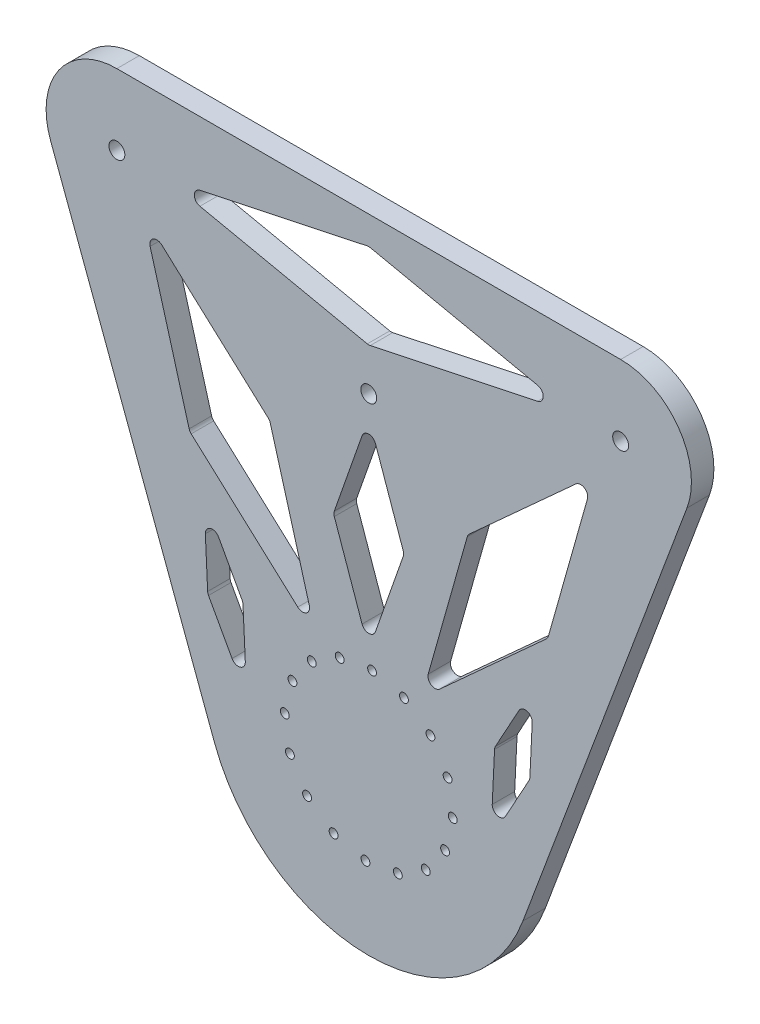
SolidWorks part; units mm, degrees
ref_plane "Front Plane" through (0, 0, 0) normal (0, 0, 1) x (1, 0, 0)
ref_plane "Top Plane" through (0, 0, 0) normal (0, 1, 0) x (1, 0, 0)
ref_plane "Right Plane" through (0, 0, 0) normal (1, 0, 0) x (0, 0, -1)
sketch "Sketch1" plane through (0, 0, 0) normal (0, 0, 1) x (1, 0, 0)
  line L0 (43.5664, -16.2548) -> (100, 135)
  line L1 (100, 135) -> (-100, 135)
  line L2 (-100, 135) -> (-43.5664, -16.2548)
  line L3 (0, 0) -> (0, 135) construction
  circle A0 centre (0, 0) radius 46.5 construction
  arc A1 (-43.5664, -16.2548) -> (43.5664, -16.2548) centre (0, 0) ccw
  dimension "D1" = 93
  dimension "D2" = 200
  dimension "D3" = 135
extrude "Boss-Extrude1" add sketch "Sketch1" along normal mid plane 6.35
fillet "Fillet1" radius 20 2 edges at (-100, 135, 0) (100, 135, 0)
sketch "Sketch2" plane through (0, 0, -3.175) normal (0, 0, -1) x (-1, 0, 0)
  line L0 (0, 135) -> (0, -46.5) construction
  line L1 (-71.1912, 135) -> (71.1912, 135) construction
  line L2 (-71.1912, 115) -> (-71.1912, 91) construction
  line L3 (-71.1912, 103) -> (0, 103) construction
  arc A0 (-43.5664, -16.2548) -> (43.5664, -16.2548) centre (0, 0) ccw construction
  circle A1 centre (-71.1912, 115) radius 2.25
  circle A2 centre (71.1912, 115) radius 2.25
  circle A3 centre (0, 91) radius 2.25
  arc A4 (-71.1912, 135) -> (-89.9295, 108.0087) centre (-71.1912, 115) ccw construction
  arc A5 (89.9295, 108.0087) -> (71.1912, 135) centre (71.1912, 115) ccw construction
  point P13 (0, 0)
  dimension "D1" = 4.5
  dimension "D2" = 44
extrude "Cut-Extrude1" cut sketch "Sketch2" against normal through all
sketch "Sketch3" plane through (0, 0, -3.175) normal (0, 0, -1) x (-1, 0, 0)
  circle A0 centre (17.4402, -16.1215) radius 1.25 construction
  circle A1 centre (22.282, -8.2203) radius 1.25 construction
  circle A2 centre (9.9432, -21.5684) radius 1.25 construction
  circle A3 centre (0.9324, -23.7317) radius 1.25 construction
  circle A4 centre (-8.2203, -22.282) radius 1.25 construction
  circle A5 centre (-16.1215, -17.4402) radius 1.25 construction
  circle A6 centre (-21.5684, -9.9432) radius 1.25 construction
  circle A7 centre (-23.7317, -0.9324) radius 1.25 construction
  circle A8 centre (-22.282, 8.2203) radius 1.25 construction
  circle A9 centre (-17.4402, 16.1215) radius 1.25 construction
  circle A10 centre (-9.9432, 21.5684) radius 1.25 construction
  circle A11 centre (-0.9324, 23.7317) radius 1.25 construction
  circle A12 centre (8.2203, 22.282) radius 1.25 construction
  circle A13 centre (16.1215, 17.4402) radius 1.25 construction
  circle A14 centre (21.5684, 9.9432) radius 1.25 construction
  circle A15 centre (23.7317, 0.9324) radius 1.25 construction
  circle A16 centre (17.4402, -16.1215) radius 1.25
  circle A17 centre (22.282, -8.2203) radius 1.25
  circle A18 centre (9.9432, -21.5684) radius 1.25
  circle A19 centre (0.9324, -23.7317) radius 1.25
  circle A20 centre (-8.2203, -22.282) radius 1.25
  circle A21 centre (-16.1215, -17.4402) radius 1.25
  circle A22 centre (-21.5684, -9.9432) radius 1.25
  circle A23 centre (-23.7317, -0.9324) radius 1.25
  circle A24 centre (-22.282, 8.2203) radius 1.25
  circle A25 centre (-17.4402, 16.1215) radius 1.25
  circle A26 centre (-9.9432, 21.5684) radius 1.25
  circle A27 centre (-0.9324, 23.7317) radius 1.25
  circle A28 centre (8.2203, 22.282) radius 1.25
  circle A29 centre (16.1215, 17.4402) radius 1.25
  circle A30 centre (21.5684, 9.9432) radius 1.25
  circle A31 centre (23.7317, 0.9324) radius 1.25
extrude "Cut-Extrude2" cut sketch "Sketch3" against normal through all both and the other way through all
sketch "Sketch4" plane through (0, 0, 3.175) normal (0, 0, 1) x (1, 0, 0)
  line L0 (-63.6967, 102.8937) -> (-50.6079, 56.4866)
  line L1 (-50.6079, 56.4866) -> (-14.9058, 24.0783)
  line L4 (0, 0) -> (-71.1912, 115) construction
  line L5 (0, 0) -> (71.1912, 115) construction
  line L6 (-63.6967, 102.8937) -> (-27.9946, 70.4854)
  line L7 (-27.9946, 70.4854) -> (-14.9058, 24.0783)
  line L8 (0, 0) -> (0, 135) construction
  line L9 (71.1912, 135) -> (-71.1912, 135) construction
  line L10 (63.6967, 102.8937) -> (50.6079, 56.4866)
  line L11 (50.6079, 56.4866) -> (14.9058, 24.0783)
  line L12 (27.9946, 70.4854) -> (14.9058, 24.0783)
  line L13 (63.6967, 102.8937) -> (27.9946, 70.4854)
  line L14 (0, 85.1838) -> (-9.9763, 56.7512)
  line L15 (-9.9763, 56.7512) -> (0, 28.3187)
  line L18 (9.9763, 56.7512) -> (0, 28.3187)
  line L19 (0, 85.1838) -> (9.9763, 56.7512)
  line L20 (-71.1912, 115) -> (71.1912, 115) construction
  line L21 (-56.9529, 115) -> (0, 127.0737)
  line L22 (-56.9529, 115) -> (0, 102.9263)
  line L23 (56.9529, 115) -> (0, 102.9263)
  line L24 (56.9529, 115) -> (0, 127.0737)
  line L25 (-46.6026, 42.2858) -> (-45.5127, 19.3978)
  line L26 (-45.5127, 19.3978) -> (-34.4825, -0.6866)
  line L29 (-34.4825, -0.6866) -> (-46.6026, 42.2858) construction
  line L30 (-35.5724, 22.2014) -> (-34.4825, -0.6866)
  line L31 (-46.6026, 42.2858) -> (-35.5724, 22.2014)
  line L32 (46.6026, 42.2858) -> (35.5724, 22.2014)
  line L33 (35.5724, 22.2014) -> (34.4825, -0.6866)
  line L34 (45.5127, 19.3978) -> (34.4825, -0.6866)
  line L35 (46.6026, 42.2858) -> (45.5127, 19.3978)
  circle A0 centre (0, 0) radius 28.3187 construction
  circle A1 centre (0, 208.5873) radius 117.5873 construction
  circle A2 centre (-71.1912, 115) radius 2.25 construction
  circle A3 centre (71.1912, 115) radius 2.25 construction
  circle A4 centre (0, 91) radius 2.25 construction
  circle A5 centre (-71.1912, 115) radius 2.25 construction
  circle A6 centre (71.1912, 115) radius 2.25 construction
  circle A7 centre (0, 91) radius 2.25 construction
  circle A8 centre (0, 208.5873) radius 123.4035 construction
  circle A9 centre (71.1912, 115) radius 14.2384 construction
  circle A10 centre (-71.1912, 115) radius 14.2384 construction
  dimension "D1" = 117.5873
extrude "Cut-Extrude3" cut sketch "Sketch4" against normal through all both and the other way through all
fillet "Fillet2" radius 2 24 edges at (50.6079, 56.4866, 0) (63.6967, 102.8937, 0) (27.9946, 70.4854, 0) (14.9058, 24.0783, 0) (-14.9058, 24.0783, 0) (-27.9946, 70.4854, 0) (-63.6967, 102.8937, 0) (-50.6079, 56.4866, 0) (9.9763, 56.7512, 0) (0, 85.1838, 0) (-9.9763, 56.7512, 0) (0, 28.3187, 0) (56.9529, 115, 0) (0, 102.9263, 0) (0, 127.0737, 0) (-56.9529, 115, 0) (45.5127, 19.3978, 0) (46.6026, 42.2858, 0) (35.5724, 22.2014, 0) (34.4825, -0.6866, 0) (-46.6026, 42.2858, 0) (-45.5127, 19.3978, 0) (-35.5724, 22.2014, 0) (-34.4825, -0.6866, 0)
ref_plane "Plane1" through (0, 103, 0) normal (0, 1, 0) x (1, 0, 0)
